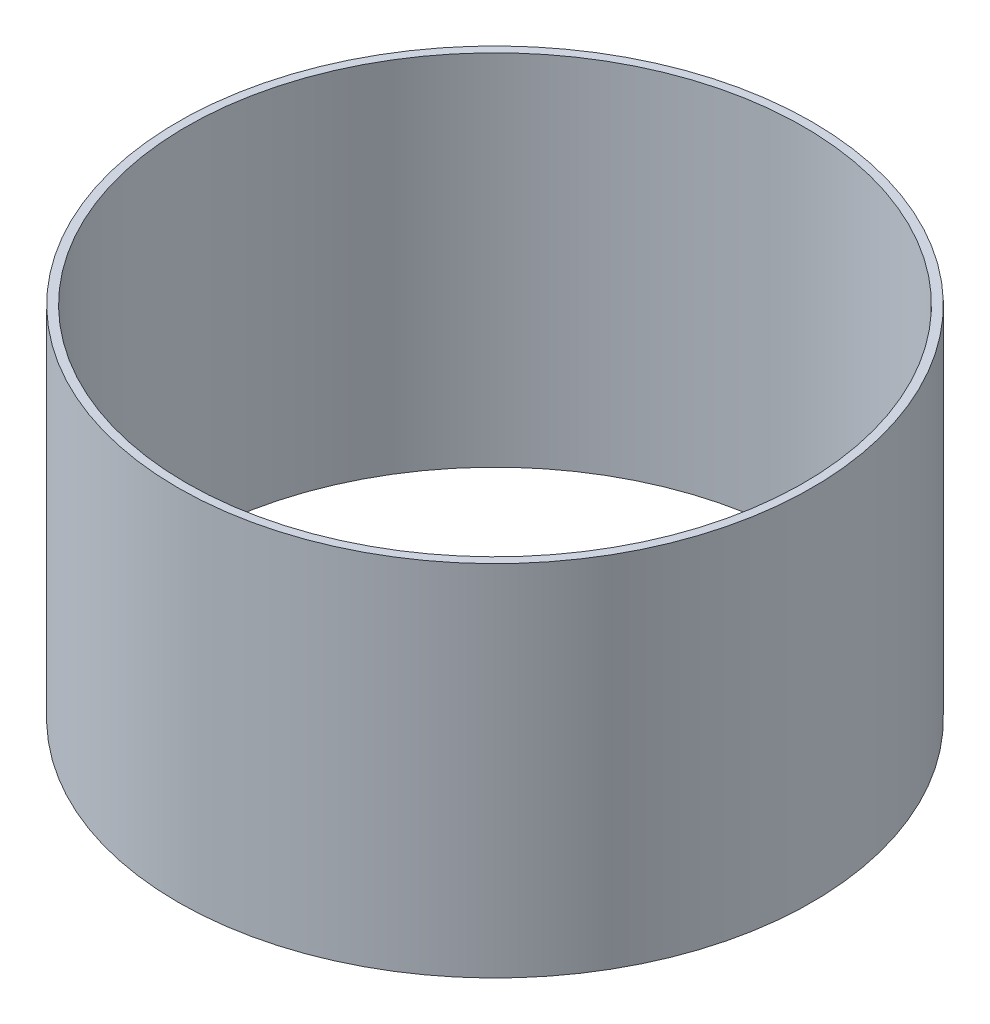
SolidWorks part; units mm, degrees
ref_plane "Front Plane" through (0, 0, 0) normal (0, 0, 1) x (1, 0, 0)
ref_plane "Top Plane" through (0, 0, 0) normal (0, 1, 0) x (1, 0, 0)
ref_plane "Right Plane" through (0, 0, 0) normal (1, 0, 0) x (0, 0, -1)
sketch "Sketch1" plane through (0, 0, 0) normal (0, 1, 0) x (1, 0, 0)
  circle A0 centre (0, 0) radius 265
  circle A1 centre (0, 0) radius 258
  dimension "D1" = 530
  dimension "D2" = 7
extrude "Boss-Extrude1" add sketch "Sketch1" along normal mid plane 300
